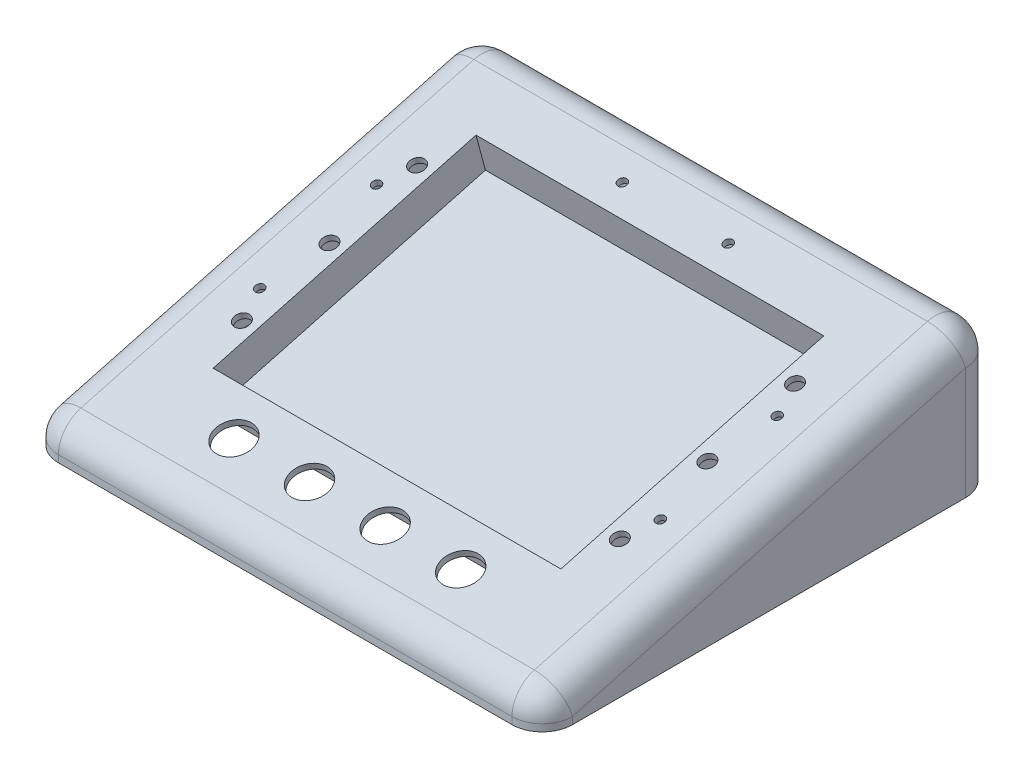
SolidWorks part; units mm, degrees
ref_plane "Front Plane" through (0, 0, 0) normal (0, 0, 1) x (1, 0, 0)
ref_plane "Top Plane" through (0, 0, 0) normal (0, 1, 0) x (1, 0, 0)
ref_plane "Right Plane" through (0, 0, 0) normal (1, 0, 0) x (0, 0, -1)
sketch "Sketch1" plane through (0, 0, 0) normal (0, 1, 0) x (1, 0, 0)
  line L1 (-85, 75) -> (85, 75)
  line L2 (-85, 75) -> (-85, -75)
  line L3 (-85, -75) -> (85, -75)
  line L4 (85, 75) -> (85, -75)
  line L5 (-85, 75) -> (85, -75) construction
  line L6 (-85, -75) -> (85, 75) construction
  point P0 (0, 0)
  dimension "D1" = 150
  dimension "D2" = 170
extrude "Boss-Extrude1" add sketch "Sketch1" along normal blind 10
sketch "Sketch2" plane through (-85, 0, 0) normal (-1, 0, 0) x (0, 0, 1)
  line L0 (-75, 10) -> (-75, 50.1924)
  line L1 (-75, 50.1924) -> (75, 10)
  line L2 (75, 10) -> (75, 0) construction
  line L3 (-75, 10) -> (75, 10) construction
  line L4 (75, 10) -> (-75, 10)
  dimension "D1" = 15
extrude "Boss-Extrude2" add sketch "Sketch2" against normal up to surface (170 mm away) up to face at (85, 5, 0)
fillet "Fillet1" radius 10 8 edges at (0, 10, 75) (85, 30.0962, 0) (-85, 30.0962, 0) (0, 50.1924, -75) (85, 5, 75) (85, 25.0962, -75) (-85, 25.0962, -75) (-85, 5, 75)
shell "Shell1" thickness 2
sketch "Sketch3" plane through (0, 28.0801, 7.524) normal (0, 0.9659, 0.2588) x (1, 0, 0)
  line L1 (-57.5, 55) -> (57.5, 55)
  line L2 (-57.5, 55) -> (-57.5, -35)
  line L3 (-57.5, -35) -> (57.5, -35)
  line L4 (57.5, 55) -> (57.5, -35)
  point P0 (0, -35)
  point P7 (57.5, 10)
  dimension "D1" = 115
  dimension "D2" = 90
  dimension "D3" = 10
extrude "Cut-Extrude1" cut sketch "Sketch3" against normal up to surface (2 mm away) up to face at (0, 27.4708, 2.0706)
sketch "Sketch4" plane through (0, 26.1483, 7.0064) normal (0, -0.9659, -0.2588) x (1, 0, 0)
  line L0 (-59.5, -57) -> (59.5, -57)
  line L1 (59.5, -57) -> (59.5, 37)
  line L2 (59.5, 37) -> (-59.5, 37)
  line L3 (-59.5, 37) -> (-59.5, -57)
  line L4 (-57.5, -55) -> (57.5, -55)
  line L5 (57.5, -55) -> (57.5, 35)
  line L6 (57.5, 35) -> (-57.5, 35)
  line L7 (-57.5, 35) -> (-57.5, -55)
  line L8 (-57.5, -55) -> (57.5, -55)
  line L9 (57.5, -55) -> (57.5, 35)
  line L10 (57.5, 35) -> (-57.5, 35)
  line L11 (-57.5, 35) -> (-57.5, -55)
  dimension "D1" = 0
  dimension "D2" = 2
extrude "Boss-Extrude3" add sketch "Sketch4" along normal blind 10
sketch "Sketch5" plane through (0, 16.489, 4.4182) normal (0, -0.9659, -0.2588) x (1, 0, 0)
  line L4 (-59.5, 37) -> (-59.5, -57)
  line L5 (-59.5, -57) -> (59.5, -57)
  line L6 (59.5, -57) -> (59.5, 37)
  line L7 (59.5, 37) -> (-59.5, 37)
  line L8 (-59.5, 37) -> (-59.5, -57)
  line L9 (-59.5, -57) -> (59.5, -57)
  line L10 (59.5, -57) -> (59.5, 37)
  line L11 (59.5, 37) -> (-59.5, 37)
  dimension "D1" = 0
extrude "Boss-Extrude4" add sketch "Sketch5" along normal blind 2
sketch "Sketch6" plane through (0, 28.0801, 7.524) normal (0, 0.9659, 0.2588) x (1, 0, 0)
  line L0 (-57.5, -35) -> (-57.5, 55) construction
  line L1 (-57.5, 55) -> (-57.5, -35) construction
  line L2 (0, -25.9381) -> (0, 25.9381) construction
  circle A0 centre (-62.5, 10) radius 2.5
  circle A1 centre (-62.5, 40) radius 2.5
  circle A2 centre (-62.5, -20) radius 2.5
  circle A3 centre (62.5, -20) radius 2.5
  circle A4 centre (62.5, 40) radius 2.5
  circle A5 centre (62.5, 10) radius 2.5
  point P9 (-57.5, 10)
  dimension "D4" = 5
  dimension "D1" = 5
  dimension "D2" = 30
  dimension "D3" = 30
extrude "Cut-Extrude2" cut sketch "Sketch6" against normal up to surface (2 mm away) up to face at (0, 27.4708, 2.0706)
sketch "Sketch7" plane through (0, 28.0801, 7.524) normal (0, 0.9659, 0.2588) x (1, 0, 0)
  line L5 (-37.5, -48.5915) -> (37.5, -48.5915) construction
  line L9 (-57.5, -35) -> (-57.5, -62.183) construction
  line L10 (-75, -62.183) -> (75, -62.183) construction
  circle A0 centre (-12.5, -48.5915) radius 6
  circle A1 centre (12.5, -48.5915) radius 6
  circle A2 centre (37.5, -48.5915) radius 6
  circle A3 centre (-37.5, -48.5915) radius 6
  point P9 (-57.5, -48.5915)
  point P12 (0, -48.5915)
  dimension "D1" = 12
  dimension "D2" = 25
  dimension "D3" = 75
  dimension "D4" = 12.5
extrude "Cut-Extrude3" cut sketch "Sketch7" against normal up to surface (2 mm away) up to face at (-62.5, 35.854, -29.2158)
sketch "Sketch9" plane through (0, 0, 0) normal (0, -1, 0) x (1, 0, 0)
  line L0 (-83, 65) -> (-83, -65) construction
  line L1 (-83, -40) -> (-73, -40)
  line L2 (-83, -40) -> (-83, -55)
  line L3 (-83, -55) -> (-73, -55)
  line L4 (-73, -40) -> (-73, -55)
  dimension "D1" = 15
  dimension "D2" = 10
  dimension "D3" = 40
extrude "Boss-Extrude5" add sketch "Sketch9" against normal blind 10
sketch "Sketch10" plane through (0, 0, 0) normal (0, -1, 0) x (1, 0, 0)
  line L8 (-75.5, -42.5) -> (-80.5, -42.5)
  line L9 (-75.5, -52.5) -> (-75.5, -42.5)
  line L10 (-80.5, -52.5) -> (-75.5, -52.5)
  line L11 (-80.5, -42.5) -> (-80.5, -52.5)
  line L12 (-75.5, -42.5) -> (-80.5, -42.5)
  line L13 (-75.5, -52.5) -> (-75.5, -42.5)
  line L14 (-80.5, -52.5) -> (-75.5, -52.5)
  line L15 (-80.5, -42.5) -> (-80.5, -52.5)
  dimension "D1" = 2.5
extrude "Cut-Extrude4" cut sketch "Sketch10" against normal blind 5
mirror "Mirror1" about plane through (0, 0, 0) normal (1, 0, 0) of "Boss-Extrude5", "Cut-Extrude4" second plane through (0, 0, 0) second plane normal (0, 0, 1)
fillet "Fillet2" radius 2 8 edges at (-73, 5, -40) (-73, 5, -55) (-73, 5, 40) (-73, 5, 55) (73, 5, -55) (73, 5, -40) (73, 5, 55) (73, 5, 40)
sketch "Sketch11" plane through (0, 28.0801, 7.524) normal (0, 0.9659, 0.2588) x (1, 0, 0)
  line L0 (-17.5, 63.7015) -> (17.5, 63.7015) construction
  line L2 (0, 55) -> (0, 72.4029) construction
  line L3 (57.5, 55) -> (-57.5, 55) construction
  line L4 (75, 72.4029) -> (-75, 72.4029) construction
  line L5 (-66.25, -10) -> (66.25, -10) construction
  line L6 (-57.5, 55) -> (-57.5, -35) construction
  line L7 (-66.25, -10) -> (-66.25, 10) construction
  line L8 (-66.25, 10) -> (-66.25, 30) construction
  circle A0 centre (-17.5, 63.7015) radius 1.5
  circle A1 centre (17.5, 63.7015) radius 1.5
  circle A3 centre (-66.25, -10) radius 1.5
  circle A4 centre (66.25, -10) radius 1.5
  circle A5 centre (-66.25, 30) radius 1.5
  circle A6 centre (66.25, 30) radius 1.5
  circle A7 centre (-62.5, 10) radius 2.5 construction
  circle A8 centre (-62.5, 10) radius 2.5 construction
  point P6 (0, 63.7015)
  point P18 (0, -10)
  point P31 (0, 0)
  point P32 (0, 0)
  dimension "D2" = 3
  dimension "D1" = 35
  dimension "D4" = 10
  dimension "D5" = 8.75
extrude "Cut-Extrude5" cut sketch "Sketch11" against normal up to surface (2 mm away) up to face at (-37.5, 12.019, 59.7377)
